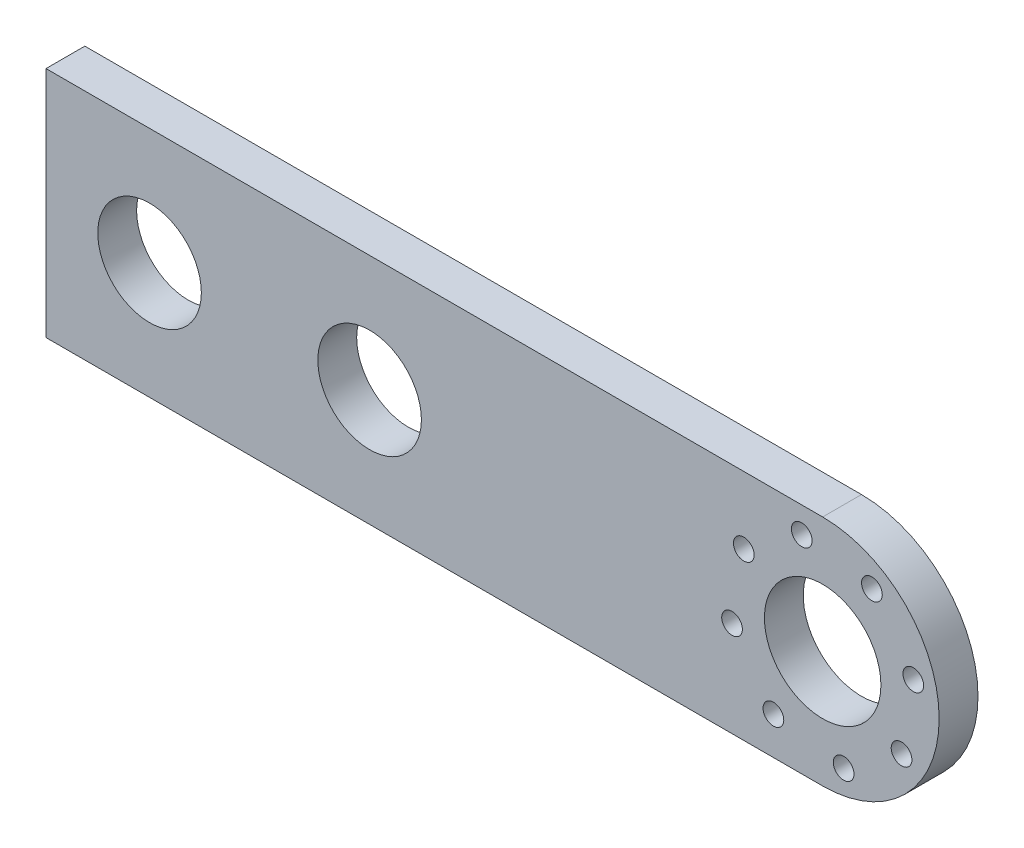
SolidWorks part; units mm, degrees
ref_plane "Plan de face" through (0, 0, 0) normal (0, 0, 1) x (1, 0, 0)
ref_plane "Plan de dessus" through (0, 0, 0) normal (0, 1, 0) x (1, 0, 0)
ref_plane "Plan de droite" through (0, 0, 0) normal (1, 0, 0) x (0, 0, -1)
sketch "Esquisse1" plane through (0, 0, 0) normal (0, 0, 1) x (1, 0, 0)
  line L5 (1.5978, 9) -> (24.5978, 9)
  line L12 (24.5978, 0) -> (22.9791, 7) construction
  line L13 (24.5978, 0) -> (28.4029, 6.0944) construction
  line L17 (-35.4022, -9) -> (24.5978, -9)
  line L20 (-7.0522, 9) -> (-16.7522, 9)
  line L23 (-35.4022, -9) -> (-35.4022, 9)
  line L24 (-35.4022, 9) -> (-16.7522, 9)
  line L25 (-7.0522, 9) -> (1.5978, 9)
  arc A1 (24.5978, 9) -> (24.5978, -9) centre (24.5978, 0) cw
  circle A2 centre (24.5978, 0) radius 4.5
  circle A11 centre (22.9791, 7) radius 0.8
  circle A12 centre (28.4029, 6.0944) radius 0.8
  circle A13 centre (31.5978, 1.6188) radius 0.8
  circle A14 centre (30.6922, -3.8051) radius 0.8
  circle A15 centre (26.2166, -7) radius 0.8
  circle A16 centre (20.7927, -6.0944) radius 0.8
  circle A17 centre (17.5978, -1.6188) radius 0.8
  circle A18 centre (18.5034, 3.8051) radius 0.8
  dimension "D1" = 9.7
  dimension "D4" = 9
  dimension "D5" = 9
  dimension "D6" = 1.6
  dimension "D2" = 60
  dimension "D7" = 7
  dimension "D9" = 45
  dimension "D8" = 8
extrude "Boss.-Extru.1" add sketch "Esquisse1" along normal blind 3
sketch "Esquisse2" plane through (0, 0, 3) normal (0, 0, 1) x (1, 0, 0)
  line L1 (-35.4022, 9) -> (-35.4022, -9) construction
  circle A0 centre (-27.4022, 0) radius 4
  circle A1 centre (-10.4022, 0) radius 4
  dimension "D1" = 8
  dimension "D2" = 8
  dimension "D3" = 17
  dimension "D4" = 8
extrude "Enlèv. mat.-Extru.1" cut sketch "Esquisse2" against normal blind 10
